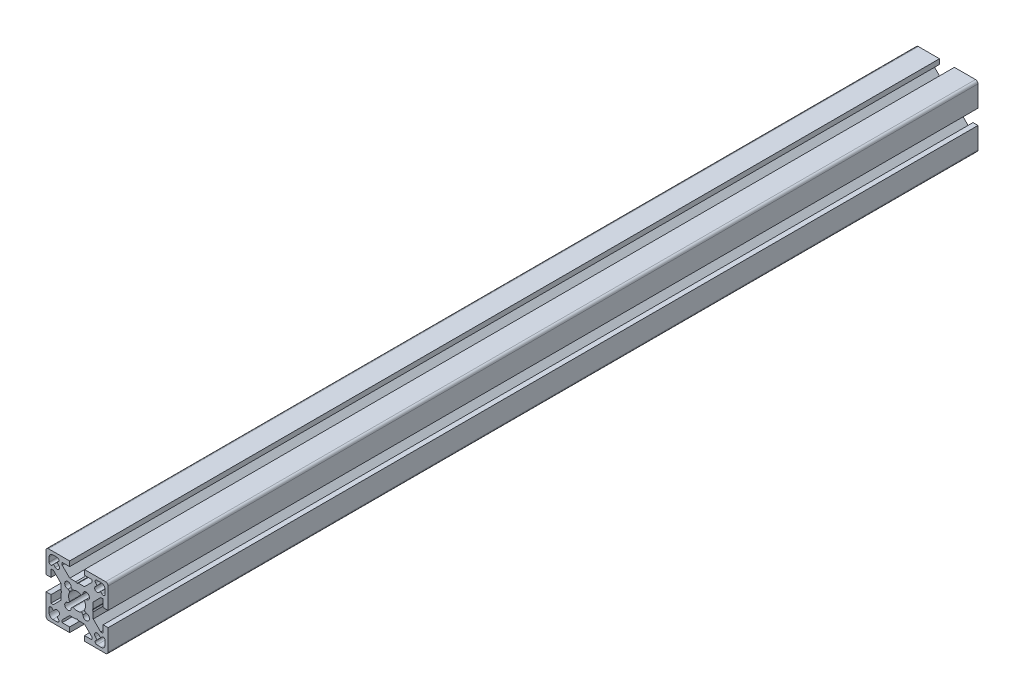
SolidWorks part; units mm, degrees
material "6061 Alloy"
ref_plane "Front Plane" through (0, 0, 0) normal (0, 0, 1) x (1, 0, 0)
ref_plane "Top Plane" through (0, 0, 0) normal (0, 1, 0) x (1, 0, 0)
ref_plane "Right Plane" through (0, 0, 0) normal (1, 0, 0) x (0, 0, -1)
ref_plane "Plane1" through (0, 0, -350) normal (0, 0, -1) x (-1, 0, 0)
sketch "Sketch1" plane through (0, 0, -350) normal (0, 0, -1) x (-1, 0, 0)
  line L0 (12.5, -3) -> (10.5, -3)
  line L1 (10.5, -3) -> (10.5, -6)
  line L2 (10.5, -6) -> (9.5355, -6)
  line L3 (9.5355, -6) -> (6.5, -2.9645)
  line L4 (6.5, -2.9645) -> (6.5, -0.5196)
  line L5 (6.5, -0.5196) -> (6.2, 0)
  line L6 (6.2, 0) -> (6.5, 0.5196)
  line L7 (6.5, 0.5196) -> (6.5, 2.9645)
  line L8 (6.5, 2.9645) -> (9.5355, 6)
  line L9 (9.5355, 6) -> (10.5, 6)
  line L10 (10.5, 6) -> (10.5, 3)
  line L11 (10.5, 3) -> (12.5, 3)
  line L12 (12.5, 3) -> (12.5, 11.5)
  line L13 (11.5, 12.5) -> (3, 12.5)
  line L14 (3, 12.5) -> (3, 10.5)
  line L15 (3, 10.5) -> (6, 10.5)
  line L16 (6, 10.5) -> (6, 9.5355)
  line L17 (6, 9.5355) -> (2.9645, 6.5)
  line L18 (2.9645, 6.5) -> (0.5196, 6.5)
  line L19 (0.5196, 6.5) -> (0, 6.2)
  line L20 (0, 6.2) -> (-0.5196, 6.5)
  line L21 (-0.5196, 6.5) -> (-2.9645, 6.5)
  line L22 (-2.9645, 6.5) -> (-6, 9.5355)
  line L23 (-6, 9.5355) -> (-6, 10.5)
  line L24 (-6, 10.5) -> (-3, 10.5)
  line L25 (-3, 10.5) -> (-3, 12.5)
  line L26 (-3, 12.5) -> (-11.5, 12.5)
  line L27 (-12.5, 11.5) -> (-12.5, 3)
  line L28 (-12.5, 3) -> (-10.5, 3)
  line L29 (-10.5, 3) -> (-10.5, 6)
  line L30 (-10.5, 6) -> (-9.5355, 6)
  line L31 (-9.5355, 6) -> (-6.5, 2.9645)
  line L32 (-6.5, 2.9645) -> (-6.5, 0.5196)
  line L33 (-6.5, 0.5196) -> (-6.2, 0)
  line L34 (-6.2, 0) -> (-6.5, -0.5196)
  line L35 (-6.5, -0.5196) -> (-6.5, -2.9645)
  line L36 (-6.5, -2.9645) -> (-9.5355, -6)
  line L37 (-9.5355, -6) -> (-10.5, -6)
  line L38 (-10.5, -6) -> (-10.5, -3)
  line L39 (-10.5, -3) -> (-12.5, -3)
  line L40 (-12.5, -3) -> (-12.5, -11.5)
  line L41 (-11.5, -12.5) -> (-3, -12.5)
  line L42 (-3, -12.5) -> (-3, -10.5)
  line L43 (-3, -10.5) -> (-6, -10.5)
  line L44 (-6, -10.5) -> (-6, -9.5355)
  line L45 (-6, -9.5355) -> (-2.9645, -6.5)
  line L46 (-2.9645, -6.5) -> (-0.5196, -6.5)
  line L47 (-0.5196, -6.5) -> (0, -6.2)
  line L48 (0, -6.2) -> (0.5196, -6.5)
  line L49 (0.5196, -6.5) -> (2.9645, -6.5)
  line L50 (2.9645, -6.5) -> (6, -9.5355)
  line L51 (6, -9.5355) -> (6, -10.5)
  line L52 (6, -10.5) -> (3, -10.5)
  line L53 (3, -10.5) -> (3, -12.5)
  line L54 (3, -12.5) -> (11.5, -12.5)
  line L55 (12.5, -11.5) -> (12.5, -3)
  line L56 (3.0878, -1.8857) -> (3.5855, -2.3834)
  line L57 (2.3834, -3.5855) -> (1.8857, -3.0878)
  line L58 (-1.8857, -3.0878) -> (-2.3834, -3.5855)
  line L59 (-3.5855, -2.3834) -> (-3.0878, -1.8857)
  line L60 (-3.0878, 1.8857) -> (-3.5855, 2.3834)
  line L61 (-2.3834, 3.5855) -> (-1.8857, 3.0878)
  line L62 (1.8857, 3.0878) -> (2.3834, 3.5855)
  line L63 (3.5855, 2.3834) -> (3.0878, 1.8857)
  line L64 (11.25, -7.9762) -> (11.25, -9.75)
  line L65 (9.75, -11.25) -> (7.9762, -11.25)
  line L66 (7.4812, -10.055) -> (8.061, -9.4752)
  line L67 (8.061, -9.4752) -> (7.3539, -8.7681)
  line L68 (8.7681, -7.3539) -> (9.4752, -8.061)
  line L69 (9.4752, -8.061) -> (10.055, -7.4812)
  line L70 (-8.061, 9.4752) -> (-7.3539, 8.7681)
  line L71 (-8.7681, 7.3539) -> (-9.4752, 8.061)
  line L72 (-9.4752, 8.061) -> (-10.055, 7.4812)
  line L73 (-11.25, 7.9762) -> (-11.25, 9.75)
  line L74 (-9.75, 11.25) -> (-7.9762, 11.25)
  line L75 (-7.4812, 10.055) -> (-8.061, 9.4752)
  line L76 (-9.4752, -8.061) -> (-8.7681, -7.3539)
  line L77 (-7.3539, -8.7681) -> (-8.061, -9.4752)
  line L78 (-8.061, -9.4752) -> (-7.4812, -10.055)
  line L79 (-7.9762, -11.25) -> (-9.75, -11.25)
  line L80 (-11.25, -9.75) -> (-11.25, -7.9762)
  line L81 (-10.055, -7.4812) -> (-9.4752, -8.061)
  line L82 (11.25, 9.75) -> (11.25, 7.9762)
  line L83 (10.055, 7.4812) -> (9.4752, 8.061)
  line L84 (9.4752, 8.061) -> (8.7681, 7.3539)
  line L85 (7.3539, 8.7681) -> (8.061, 9.4752)
  line L86 (8.061, 9.4752) -> (7.4812, 10.055)
  line L87 (7.9762, 11.25) -> (9.75, 11.25)
  arc A0 (12.5, 11.5) -> (11.5, 12.5) centre (11.5, 11.5) ccw
  arc A1 (-11.5, 12.5) -> (-12.5, 11.5) centre (-11.5, 11.5) ccw
  arc A2 (-12.5, -11.5) -> (-11.5, -12.5) centre (-11.5, -11.5) ccw
  arc A3 (11.5, -12.5) -> (12.5, -11.5) centre (11.5, -11.5) ccw
  arc A4 (3.0323, -1.5378) -> (3.0878, -1.8857) centre (3.2999, -1.6735) ccw
  arc A5 (3.5855, -2.3834) -> (2.3834, -3.5855) centre (3.68, -3.68) cw
  arc A6 (1.8857, -3.0878) -> (1.5378, -3.0323) centre (1.6735, -3.2999) ccw
  arc A7 (1.5378, -3.0323) -> (-1.5378, -3.0323) centre (0, 0) cw
  arc A8 (-1.5378, -3.0323) -> (-1.8857, -3.0878) centre (-1.6735, -3.2999) ccw
  arc A9 (-2.3834, -3.5855) -> (-3.5855, -2.3834) centre (-3.68, -3.68) cw
  arc A10 (-3.0878, -1.8857) -> (-3.0323, -1.5378) centre (-3.2999, -1.6735) ccw
  arc A11 (-3.0323, -1.5378) -> (-3.0323, 1.5378) centre (0, 0) cw
  arc A12 (-3.0323, 1.5378) -> (-3.0878, 1.8857) centre (-3.2999, 1.6735) ccw
  arc A13 (-3.5855, 2.3834) -> (-2.3834, 3.5855) centre (-3.68, 3.68) cw
  arc A14 (-1.8857, 3.0878) -> (-1.5378, 3.0323) centre (-1.6735, 3.2999) ccw
  arc A15 (-1.5378, 3.0323) -> (1.5378, 3.0323) centre (0, 0) cw
  arc A16 (1.5378, 3.0323) -> (1.8857, 3.0878) centre (1.6735, 3.2999) ccw
  arc A17 (2.3834, 3.5855) -> (3.5855, 2.3834) centre (3.68, 3.68) cw
  arc A18 (3.0878, 1.8857) -> (3.0323, 1.5378) centre (3.2999, 1.6735) ccw
  arc A19 (3.0323, 1.5378) -> (3.0323, -1.5378) centre (0, 0) cw
  arc A20 (11.25, -9.75) -> (9.75, -11.25) centre (9.75, -9.75) cw
  arc A21 (7.9762, -11.25) -> (7.4812, -10.055) centre (7.9762, -10.55) cw
  arc A22 (7.3539, -8.7681) -> (8.7681, -7.3539) centre (8.061, -8.061) cw
  arc A23 (10.055, -7.4812) -> (11.25, -7.9762) centre (10.55, -7.9762) cw
  arc A24 (-7.3539, 8.7681) -> (-8.7681, 7.3539) centre (-8.061, 8.061) cw
  arc A25 (-10.055, 7.4812) -> (-11.25, 7.9762) centre (-10.55, 7.9762) cw
  arc A26 (-11.25, 9.75) -> (-9.75, 11.25) centre (-9.75, 9.75) cw
  arc A27 (-7.9762, 11.25) -> (-7.4812, 10.055) centre (-7.9762, 10.55) cw
  arc A28 (-8.7681, -7.3539) -> (-7.3539, -8.7681) centre (-8.061, -8.061) cw
  arc A29 (-7.4812, -10.055) -> (-7.9762, -11.25) centre (-7.9762, -10.55) cw
  arc A30 (-9.75, -11.25) -> (-11.25, -9.75) centre (-9.75, -9.75) cw
  arc A31 (-11.25, -7.9762) -> (-10.055, -7.4812) centre (-10.55, -7.9762) cw
  arc A32 (9.75, 11.25) -> (11.25, 9.75) centre (9.75, 9.75) cw
  arc A33 (11.25, 7.9762) -> (10.055, 7.4812) centre (10.55, 7.9762) cw
  arc A34 (8.7681, 7.3539) -> (7.3539, 8.7681) centre (8.061, 8.061) cw
  arc A35 (7.4812, 10.055) -> (7.9762, 11.25) centre (7.9762, 10.55) cw
extrude "Boss-Extrude1" add sketch "Sketch1" against normal blind 350
